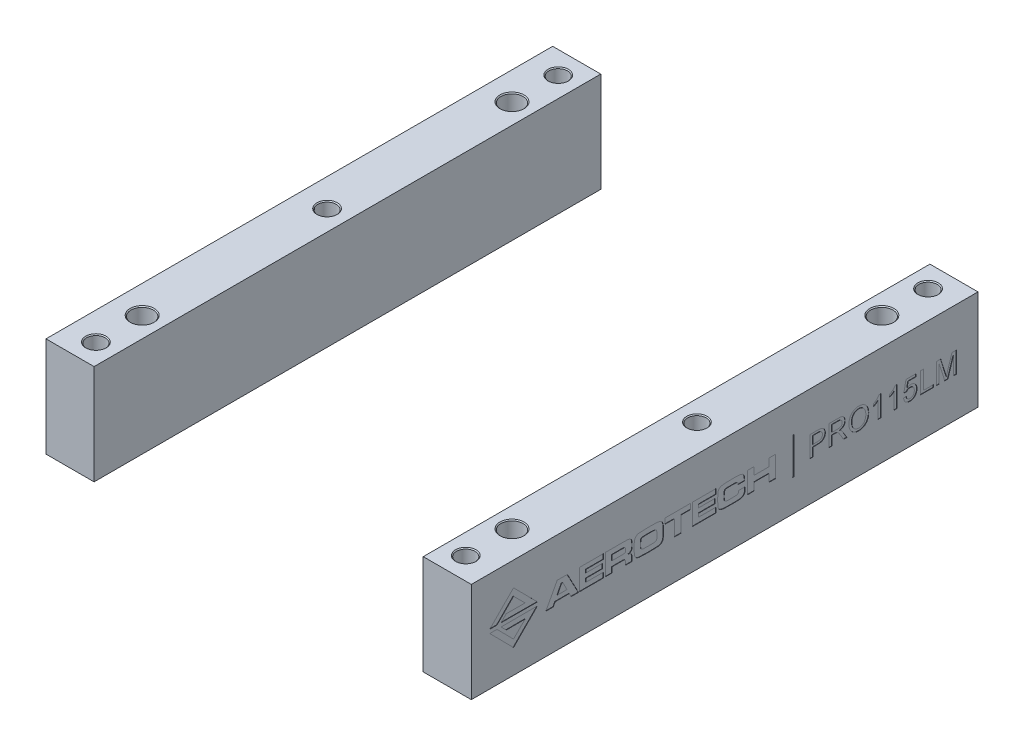
SolidWorks part; units mm, degrees
material "Aluminum Black Anodize"
ref_plane "Front" through (0, 0, 0) normal (0, 0, 1) x (1, 0, 0)
ref_plane "Top" through (0, 0, 0) normal (0, 1, 0) x (1, 0, 0)
ref_plane "Right" through (0, 0, 0) normal (1, 0, 0) x (0, 0, -1)
sketch "Sketch1" plane through (0, 0, 0) normal (0, 0, 1) x (1, 0, 0)
  line L0 (0, 0) -> (0, -37) construction
  line L1 (-57.5, -10) -> (-44.5, -10)
  line L2 (-57.5, -10) -> (-57.5, -37)
  line L3 (-57.5, -37) -> (-44.5, -37)
  line L4 (-44.5, -10) -> (-44.5, -37)
  line L5 (44.5, -10) -> (57.5, -10)
  line L6 (44.5, -10) -> (44.5, -37)
  line L7 (44.5, -37) -> (57.5, -37)
  line L8 (57.5, -10) -> (57.5, -37)
  dimension "D1" = 27
  dimension "D2" = 13
  dimension "D3" = 89
  dimension "D4" = 10
extrude "Extrude1" add sketch "Sketch1" along normal mid plane 137
hole_wizard "M5x0.8 Tapped Hole1" positions "Sketch4" profile "Sketch3" tap size "M5x0.8" standard "ANSI Metric"
sketch "Sketch4" plane through (0, -10, 0) normal (0, 1, 0) x (-1, 0, 0)
  line L0 (50, 62.5) -> (50, -62.5) construction
  line L1 (50, -62.5) -> (-50, -62.5) construction
  line L2 (-50, -62.5) -> (-50, 62.5) construction
  line L3 (-50, 62.5) -> (50, 62.5) construction
  line L4 (50, 62.5) -> (-50, -62.5) construction
  point P0 (50, -62.5)
  point P1 (-50, -62.5)
  point P3 (-50, 0)
  point P5 (50, 0)
  point P7 (50, 62.5)
  point P9 (-50, 62.5)
  dimension "D1" = 100
  dimension "D2" = 125
sketch "Sketch3" plane through (-50, -10, -62.5) normal (1, 0, 0) x (0, 0, 1)
  line L0 (0, 0) -> (0, 9.4618)
  line L1 (0, 9.4618) -> (2.1, 8.2)
  line L2 (2.1, 8.2) -> (2.1, 5.8)
  line L3 (2.1, 5.8) -> (2.5, 5.8)
  line L5 (2.5, 5.8) -> (2.5, 0.25)
  line L6 (2.5, 0.25) -> (2.75, 0)
  line L7 (2.75, 0) -> (0, 0)
  line L8 (-2.5, 0.25) -> (-2.75, 0) construction
  line L10 (0, 9.4618) -> (-2.1, 8.2) construction
  line L11 (0, -6.35) -> (0, 107.95) construction
  dimension "Tap Drill Dia." = 4.2
  dimension "Tap Drill Depth" = 8.2
  dimension "Thread Major Dia." = 5
  dimension "Thread Depth" = 5.8
  dimension "Near C'Sink Dia." = 5.5
  dimension "Near C'Sink Angle" = 90
  dimension "Drill Angle" = 118
hole_wizard "M6x1.0 Tapped Hole1" positions "Sketch6" profile "Sketch5" tap size "M6x1.0" standard "ANSI Metric"
sketch "Sketch6" plane through (0, -10, 0) normal (0, 1, 0) x (-1, 0, 0)
  line L0 (50, -50) -> (-50, -50) construction
  line L1 (-50, -50) -> (-50, 50) construction
  line L2 (-50, 50) -> (50, 50) construction
  line L3 (50, 50) -> (50, -50) construction
  line L4 (50, -50) -> (-50, 50) construction
  point P0 (50, -50)
  point P1 (-50, -50)
  point P3 (-50, 50)
  point P5 (50, 50)
  dimension "D1" = 100
  dimension "D2" = 100
sketch "Sketch5" plane through (-50, -10, -50) normal (1, 0, 0) x (0, 0, 1)
  line L0 (0, 0) -> (0, 11.5022)
  line L1 (0, 11.5022) -> (2.5, 10)
  line L2 (2.5, 10) -> (2.5, 7)
  line L3 (2.5, 7) -> (3, 7)
  line L5 (3, 7) -> (3, 0.25)
  line L6 (3, 0.25) -> (3.25, 0)
  line L7 (3.25, 0) -> (0, 0)
  line L8 (-3, 0.25) -> (-3.25, 0) construction
  line L10 (0, 11.5022) -> (-2.5, 10) construction
  line L11 (0, -6.35) -> (0, 107.95) construction
  dimension "Tap Drill Dia." = 5
  dimension "Tap Drill Depth" = 10
  dimension "Thread Major Dia." = 6
  dimension "Thread Depth" = 7
  dimension "Near C'Sink Dia." = 6.5
  dimension "Near C'Sink Angle" = 90
  dimension "Drill Angle" = 118
sketch "Sketch8" plane through (57.5, 0, 0) normal (1, 0, 0) x (0, 0, -1)
  line L5 (-68.5, -37) -> (-68.5, -10) construction
  line L6 (-68.5, -10) -> (68.5, -10) construction
  line L12 (-63.5, -16.5049) -> (63.5, -16.5049) construction
  line L13 (-63.5, -16.5049) -> (-63.5, -30.4951) construction
  line L14 (-63.5, -30.4951) -> (63.5, -30.4951) construction
  line L15 (63.5, -16.5049) -> (63.5, -30.4951) construction
  line L16 (0, -30.4951) -> (0, -10) construction
  line L17 (-63.5, -23.5) -> (-68.5, -23.5) construction
  line L18 (-48.348, -26.3532) -> (92.4372, -26.3532) construction
  text T0 "PRO115LM" font "Arial" height in points 22
  point P14 (42.2576, 86.3605)
  point P15 (42.2586, 86.3605)
  point P16 (42.2586, 86.3595)
  line B0 (-57.0873, -30.4951) -> (-50.6303, -23.9713)
  line B1 (-50.6303, -23.9713) -> (-60.452, -24.0011)
  line B2 (-60.452, -24.0011) -> (-59.05, -25.4103)
  line B3 (-59.05, -25.4103) -> (-53.9513, -25.3879)
  line B4 (-53.9513, -25.3879) -> (-57.0945, -28.5095)
  line B5 (-57.0945, -28.5095) -> (-61.5671, -24.0011)
  line B6 (-61.5671, -24.0011) -> (-63.5, -24.0083)
  line B7 (-63.5, -24.0083) -> (-57.0873, -30.4951)
  line B8 (-57.0873, -16.5049) -> (-50.6303, -23.0285)
  line B9 (-50.6303, -23.0285) -> (-60.452, -22.9986)
  line B10 (-60.452, -22.9986) -> (-59.05, -21.5893)
  line B11 (-59.05, -21.5893) -> (-53.9513, -21.6119)
  line B12 (-53.9513, -21.6119) -> (-57.0945, -18.4903)
  line B13 (-57.0945, -18.4903) -> (-61.5671, -22.9986)
  line B14 (-61.5671, -22.9986) -> (-63.5, -22.9915)
  line B15 (-63.5, -22.9915) -> (-57.0873, -16.5049)
  line B16 (-41.5139, -26.3532) -> (-42.01, -25.3896)
  line B17 (-42.01, -25.3896) -> (-45.8382, -25.3896)
  line B18 (-45.8382, -25.3896) -> (-46.3343, -26.3532)
  line B19 (-46.3343, -26.3532) -> (-48.348, -26.3532)
  line B20 (-48.348, -26.3532) -> (-45.2787, -20.6469)
  line B21 (-45.2787, -20.6469) -> (-42.5399, -20.6469)
  line B22 (-42.5399, -20.6469) -> (-39.5128, -26.3532)
  line B23 (-39.5128, -26.3532) -> (-41.5139, -26.3532)
  line B24 (-42.6287, -24.137) -> (-43.7439, -21.9743)
  line B25 (-43.7439, -21.9743) -> (-44.0957, -21.9743)
  line B26 (-44.0957, -21.9743) -> (-45.2109, -24.137)
  line B27 (-45.2109, -24.137) -> (-42.6287, -24.137)
  line B28 (-39.2288, -20.6469) -> (-32.8157, -20.6469)
  line B29 (-32.8157, -20.6469) -> (-32.8157, -21.985)
  line B30 (-32.8157, -21.985) -> (-37.4944, -21.985)
  line B31 (-37.4944, -21.985) -> (-37.4944, -22.8094)
  line B32 (-37.4944, -22.8094) -> (-33.0514, -22.8094)
  line B33 (-33.0514, -22.8094) -> (-33.0514, -24.0619)
  line B34 (-33.0514, -24.0619) -> (-37.4944, -24.0619)
  line B35 (-37.4944, -24.0619) -> (-37.4944, -24.9936)
  line B36 (-37.4944, -24.9936) -> (-32.7835, -24.9936)
  line B37 (-32.7835, -24.9936) -> (-32.7835, -26.3532)
  line B38 (-32.7835, -26.3532) -> (-39.2288, -26.3532)
  line B39 (-39.2288, -26.3532) -> (-39.2288, -20.6469)
  line B40 (-32.2072, -26.3532) -> (-32.2072, -20.6469)
  line B41 (-32.2072, -20.6469) -> (-27.9447, -20.6469)
  line B42 (-25.0662, -25.8247) -> (-25.0662, -26.3532)
  line B43 (-25.0662, -26.3532) -> (-26.8005, -26.3532)
  line B44 (-26.8005, -26.3532) -> (-26.8005, -26.0535)
  line B45 (-27.9575, -24.9078) -> (-30.4405, -24.9078)
  line B46 (-30.4405, -24.9078) -> (-30.4405, -26.3532)
  line B47 (-30.4405, -26.3532) -> (-32.2072, -26.3532)
  line B48 (-30.4405, -23.484) -> (-27.9618, -23.484)
  line B49 (-27.9659, -22.0706) -> (-30.4405, -22.0706)
  line B50 (-30.4405, -22.0706) -> (-30.4405, -23.484)
  line B51 (-16.1737, -20.6469) -> (-9.1712, -20.6469)
  line B52 (-9.1712, -20.6469) -> (-9.1712, -22.1028)
  line B53 (-9.1712, -22.1028) -> (-11.7411, -22.1028)
  line B54 (-11.7411, -22.1028) -> (-11.7411, -26.3532)
  line B55 (-11.7411, -26.3532) -> (-13.5932, -26.3532)
  line B56 (-13.5932, -26.3532) -> (-13.5932, -22.1028)
  line B57 (-13.5932, -22.1028) -> (-16.1737, -22.1028)
  line B58 (-16.1737, -22.1028) -> (-16.1737, -20.6469)
  line B59 (-8.7626, -20.6469) -> (-2.3497, -20.6469)
  line B60 (-2.3497, -20.6469) -> (-2.3497, -21.985)
  line B61 (-2.3497, -21.985) -> (-7.0284, -21.985)
  line B62 (-7.0284, -21.985) -> (-7.0284, -22.8094)
  line B63 (-7.0284, -22.8094) -> (-2.5854, -22.8094)
  line B64 (-2.5854, -22.8094) -> (-2.5854, -24.0619)
  line B65 (-2.5854, -24.0619) -> (-7.0284, -24.0619)
  line B66 (-7.0284, -24.0619) -> (-7.0284, -24.9936)
  line B67 (-7.0284, -24.9936) -> (-2.3177, -24.9936)
  line B68 (-2.3177, -24.9936) -> (-2.3177, -26.3532)
  line B69 (-2.3177, -26.3532) -> (-8.7626, -26.3532)
  line B70 (-8.7626, -26.3532) -> (-8.7626, -20.6469)
  line B71 (3.7357, -24.1477) -> (5.4996, -24.1477)
  line B72 (5.4062, -22.6916) -> (3.6426, -22.6916)
  line B73 (6.1269, -20.6469) -> (7.9793, -20.6469)
  line B74 (7.9793, -20.6469) -> (7.9793, -22.6916)
  line B75 (7.9793, -22.6916) -> (11.9619, -22.6916)
  line B76 (11.9619, -22.6916) -> (11.9619, -20.6469)
  line B77 (11.9619, -20.6469) -> (13.8143, -20.6469)
  line B78 (13.8143, -20.6469) -> (13.8143, -26.3532)
  line B79 (13.8143, -26.3532) -> (11.9619, -26.3532)
  line B80 (11.9619, -26.3532) -> (11.9619, -24.2868)
  line B81 (11.9619, -24.2868) -> (7.9793, -24.2868)
  line B82 (7.9793, -24.2868) -> (7.9793, -26.3532)
  line B83 (7.9793, -26.3532) -> (6.1269, -26.3532)
  line B84 (6.1269, -26.3532) -> (6.1269, -20.6469)
  line B85 (18.7267, -28.3892) -> (18.3739, -28.3892)
  line B86 (18.3739, -28.3892) -> (18.3739, -18.5115)
  line B87 (18.3739, -18.5115) -> (18.7267, -18.5115)
  line B88 (18.7267, -18.5115) -> (18.7267, -28.3892)
  spline B89 degree 3 poles (-27.9447, -20.6469) (-26.9455, -20.6495) (-26.3471, -20.6595) (-26.1495, -20.6765) knots 2 2 2 2 3 3 3 3
  spline B90 degree 3 poles (-26.1495, -20.6765) (-25.9517, -20.6936) (-25.7614, -20.7587) (-25.5776, -20.8721) knots 3 3 3 3 4 4 4 4
  spline B91 degree 3 poles (-25.5776, -20.8721) (-25.3576, -21.0023) (-25.2067, -21.183) (-25.1248, -21.414) knots 4 4 4 4 5 5 5 5
  spline B92 degree 3 poles (-25.1248, -21.414) (-25.0429, -21.6448) (-25.0019, -22.007) (-25.0019, -22.4999) knots 5 5 5 5 6 6 6 6
  spline B93 degree 3 poles (-25.0019, -22.4999) (-25.0019, -22.9164) (-25.028, -23.2226) (-25.0801, -23.4182) knots 6 6 6 6 7 7 7 7
  spline B94 degree 3 poles (-25.0801, -23.4182) (-25.1323, -23.6137) (-25.2307, -23.7711) (-25.3745, -23.8901) knots 7 7 7 7 8 8 8 8
  spline B95 degree 3 poles (-25.3745, -23.8901) (-25.5295, -24.0143) (-25.7642, -24.1008) (-26.0773, -24.149) knots 8 8 8 8 9 9 9 9
  spline B96 degree 3 poles (-26.0773, -24.149) (-25.708, -24.1777) (-25.4427, -24.2819) (-25.282, -24.462) knots 9 9 9 9 10 10 10 10
  spline B97 degree 3 poles (-25.282, -24.462) (-25.1888, -24.5697) (-25.1296, -24.7008) (-25.1044, -24.856) knots 10 10 10 10 11 11 11 11
  spline B98 degree 3 poles (-25.1044, -24.856) (-25.0789, -25.011) (-25.0662, -25.334) (-25.0662, -25.8247) knots 11 11 11 11 12 12 12 12
  spline B99 degree 3 poles (-26.8005, -26.0535) (-26.8005, -25.735) (-26.8125, -25.5081) (-26.8366, -25.3729) knots 15 15 15 15 16 16 16 16
  spline B100 degree 3 poles (-26.8366, -25.3729) (-26.8607, -25.2377) (-26.905, -25.1345) (-26.9699, -25.0644) knots 16 16 16 16 17 17 17 17
  spline B101 degree 3 poles (-26.9699, -25.0644) (-27.0351, -24.9969) (-27.1248, -24.9538) (-27.2392, -24.9354) knots 17 17 17 17 18 18 18 18
  spline B102 degree 3 poles (-27.2392, -24.9354) (-27.3535, -24.9171) (-27.5931, -24.9078) (-27.9575, -24.9078) knots 18 18 18 18 19 19 19 19
  spline B103 degree 3 poles (-27.9618, -23.484) (-27.5341, -23.4753) (-27.2791, -23.4676) (-27.1965, -23.4604) knots 1 1 1 1 2 2 2 2
  spline B104 degree 3 poles (-27.1965, -23.4604) (-27.1139, -23.4535) (-27.0435, -23.4314) (-26.9846, -23.3942) knots 2 2 2 2 3 3 3 3
  spline B105 degree 3 poles (-26.9846, -23.3942) (-26.9091, -23.3488) (-26.8563, -23.2792) (-26.8254, -23.1851) knots 3 3 3 3 4 4 4 4
  spline B106 degree 3 poles (-26.8254, -23.1851) (-26.7946, -23.0911) (-26.7791, -22.9488) (-26.7791, -22.7581) knots 4 4 4 4 5 5 5 5
  spline B107 degree 3 poles (-26.7791, -22.7581) (-26.7791, -22.5674) (-26.7968, -22.4258) (-26.8318, -22.3333) knots 5 5 5 5 6 6 6 6
  spline B108 degree 3 poles (-26.8318, -22.3333) (-26.8666, -22.2408) (-26.9272, -22.1745) (-27.014, -22.1347) knots 6 6 6 6 7 7 7 7
  spline B109 degree 3 poles (-27.014, -22.1347) (-27.0757, -22.1063) (-27.1489, -22.0892) (-27.2342, -22.0835) knots 7 7 7 7 8 8 8 8
  spline B110 degree 3 poles (-27.2342, -22.0835) (-27.3196, -22.078) (-27.5636, -22.0737) (-27.9659, -22.0706) knots 8 8 8 8 9 9 9 9
  spline B111 degree 3 poles (-23.0861, -20.6547) (-22.6197, -20.5925) (-21.7603, -20.5611) (-20.5078, -20.5611) knots 11 11 11 11 12 12 12 12
  spline B112 degree 3 poles (-24.3286, -21.6016) (-24.1758, -21.0581) (-23.7619, -20.7425) (-23.0861, -20.6547) knots 10 10 10 10 11 11 11 11
  spline B113 degree 3 poles (-24.3286, -25.4025) (-24.433, -25.0291) (-24.4852, -24.3831) (-24.4852, -23.4661) (-24.4852, -22.5941) (-24.433, -21.9726) (-24.3286, -21.6016) knots 8 8 8 8 9 9 9 10 10 10 10
  spline B114 degree 3 poles (-23.0861, -26.3539) (-23.7619, -26.2633) (-24.1758, -25.9463) (-24.3286, -25.4025) knots 7 7 7 7 8 8 8 8
  spline B115 degree 3 poles (-17.9298, -26.3539) (-18.3992, -26.4106) (-19.2527, -26.4386) (-20.4907, -26.4386) (-21.752, -26.4386) (-22.6169, -26.4106) (-23.0861, -26.3539) knots 5 5 5 5 6 6 6 7 7 7 7
  spline B116 degree 3 poles (-16.6874, -25.4025) (-16.8402, -25.9463) (-17.2544, -26.2633) (-17.9298, -26.3539) knots 4 4 4 4 5 5 5 5
  spline B117 degree 3 poles (-16.6874, -21.6016) (-16.5826, -21.9755) (-16.5305, -22.6084) (-16.5305, -23.5002) (-16.5305, -24.3947) (-16.5826, -25.0291) (-16.6874, -25.4025) knots 2 2 2 2 3 3 3 4 4 4 4
  spline B118 degree 3 poles (-17.9298, -20.6547) (-17.2544, -20.7425) (-16.8402, -21.0581) (-16.6874, -21.6016) knots 1 1 1 1 2 2 2 2
  spline B119 degree 3 poles (-20.5078, -20.5611) (-19.2588, -20.5611) (-18.3992, -20.5925) (-17.9298, -20.6547) knots 0 0 0 0 1 1 1 1
  spline B120 degree 3 poles (-18.9535, -22.0939) (-19.1682, -22.0641) (-19.6848, -22.0493) (-20.5037, -22.0493) knots 13 13 13 13 14 14 14 14
  spline B121 degree 3 poles (-18.4917, -22.3214) (-18.5853, -22.1994) (-18.7389, -22.1237) (-18.9535, -22.0939) knots 12 12 12 12 13 13 13 13
  spline B122 degree 3 poles (-18.3393, -22.7571) (-18.3677, -22.5631) (-18.4185, -22.4175) (-18.4917, -22.3214) knots 11 11 11 11 12 12 12 12
  spline B123 degree 3 poles (-18.3522, -24.4107) (-18.3155, -24.2593) (-18.2969, -24.0092) (-18.2969, -23.6605) (-18.2969, -23.2523) (-18.3114, -22.9512) (-18.3393, -22.7571) knots 9 9 9 9 10 10 10 11 11 11 11
  spline B124 degree 3 poles (-18.5596, -24.7573) (-18.458, -24.6779) (-18.3889, -24.5626) (-18.3522, -24.4107) knots 8 8 8 8 9 9 9 9
  spline B125 degree 3 poles (-19.0808, -24.9231) (-18.8464, -24.8977) (-18.6726, -24.8424) (-18.5596, -24.7573) knots 7 7 7 7 8 8 8 8
  spline B126 degree 3 poles (-22.0243, -24.9106) (-21.7613, -24.9445) (-21.2518, -24.9614) (-20.4949, -24.9614) (-19.7864, -24.9614) (-19.3149, -24.9488) (-19.0808, -24.9231) knots 5 5 5 5 6 6 6 7 7 7 7
  spline B127 degree 3 poles (-22.6636, -24.413) (-22.5931, -24.7051) (-22.3799, -24.8706) (-22.0243, -24.9106) knots 4 4 4 4 5 5 5 5
  spline B128 degree 3 poles (-22.6171, -22.4935) (-22.6848, -22.6876) (-22.7187, -23.0752) (-22.7187, -23.6562) (-22.7187, -24.0049) (-22.7003, -24.2571) (-22.6636, -24.413) knots 2 2 2 2 3 3 3 4 4 4 4
  spline B129 degree 3 poles (-22.1892, -22.1216) (-22.4066, -22.1754) (-22.5494, -22.2995) (-22.6171, -22.4935) knots 1 1 1 1 2 2 2 2
  spline B130 degree 3 poles (-20.5037, -22.0493) (-21.4385, -22.0493) (-22, -22.0734) (-22.1892, -22.1216) knots 0 0 0 0 1 1 1 1
  spline B131 degree 3 poles (5.4996, -24.1477) (5.5082, -24.4253) (5.5126, -24.6055) (5.5126, -24.6877) knots 1 1 1 1 2 2 2 2
  spline B132 degree 3 poles (5.5126, -24.6877) (5.5126, -25.1297) (5.4461, -25.4752) (5.3135, -25.7247) knots 2 2 2 2 3 3 3 3
  spline B133 degree 3 poles (5.3135, -25.7247) (5.1668, -26.0025) (4.8798, -26.1908) (4.4529, -26.2902) knots 3 3 3 3 4 4 4 4
  spline B134 degree 3 poles (4.4529, -26.2902) (4.0268, -26.3892) (3.2899, -26.4386) (2.2419, -26.4386) knots 4 4 4 4 5 5 5 5
  spline B135 degree 3 poles (2.2419, -26.4386) (1.1401, -26.4386) (0.355, -26.4187) (-0.1121, -26.3796) knots 5 5 5 5 6 6 6 6
  spline B136 degree 3 poles (-0.1121, -26.3796) (-0.5797, -26.3401) (-0.9318, -26.2595) (-1.1695, -26.1377) knots 6 6 6 6 7 7 7 7
  spline B137 degree 3 poles (-1.1695, -26.1377) (-1.3813, -26.0306) (-1.5395, -25.8847) (-1.6438, -25.7012) knots 7 7 7 7 8 8 8 8
  spline B138 degree 3 poles (-1.6438, -25.7012) (-1.7482, -25.5174) (-1.8161, -25.2644) (-1.8471, -24.9421) knots 8 8 8 8 9 9 9 9
  spline B139 degree 3 poles (-1.8471, -24.9421) (-1.8729, -24.6848) (-1.885, -24.2167) (-1.885, -23.5381) knots 9 9 9 9 10 10 10 10
  spline B140 degree 3 poles (-1.885, -23.5381) (-1.885, -22.8768) (-1.8729, -22.3996) (-1.8471, -22.107) knots 10 10 10 10 11 11 11 11
  spline B141 degree 3 poles (-1.8471, -22.107) (-1.822, -21.8143) (-1.7724, -21.5876) (-1.6986, -21.4264) knots 11 11 11 11 12 12 12 12
  spline B142 degree 3 poles (-1.6986, -21.4264) (-1.5377, -21.0645) (-1.2118, -20.8299) (-0.7206, -20.7222) knots 12 12 12 12 13 13 13 13
  spline B143 degree 3 poles (-0.7206, -20.7222) (-0.229, -20.6151) (0.7622, -20.5611) (2.2539, -20.5611) knots 13 13 13 13 14 14 14 14
  spline B144 degree 3 poles (2.2539, -20.5611) (2.9988, -20.5611) (3.5417, -20.5773) (3.8807, -20.6097) knots 14 14 14 14 15 15 15 15
  spline B145 degree 3 poles (3.8807, -20.6097) (4.2194, -20.6421) (4.4888, -20.7052) (4.6896, -20.7984) knots 15 15 15 15 16 16 16 16
  spline B146 degree 3 poles (4.6896, -20.7984) (4.9525, -20.9198) (5.1371, -21.1013) (5.2446, -21.3427) knots 16 16 16 16 17 17 17 17
  spline B147 degree 3 poles (5.2446, -21.3427) (5.3518, -21.584) (5.4059, -21.9392) (5.4059, -22.4079) knots 17 17 17 17 18 18 18 18
  spline B148 degree 3 poles (5.4059, -22.4079) (5.4059, -22.4334) (5.4059, -22.5278) (5.4062, -22.6916) knots 18 18 18 18 19 19 19 19
  spline B149 degree 3 poles (3.6426, -22.6916) (3.634, -22.5026) (3.622, -22.3758) (3.6065, -22.3109) knots 20 20 20 20 21 21 21 21
  spline B150 degree 3 poles (3.6065, -22.3109) (3.591, -22.246) (3.5593, -22.1938) (3.5114, -22.1542) knots 21 21 21 21 22 22 22 22
  spline B151 degree 3 poles (3.5114, -22.1542) (3.4432, -22.0951) (3.2726, -22.052) (2.9988, -22.0251) knots 22 22 22 22 23 23 23 23
  spline B152 degree 3 poles (2.9988, -22.0251) (2.7245, -21.9986) (2.3097, -21.985) (1.7534, -21.985) knots 23 23 23 23 24 24 24 24
  spline B153 degree 3 poles (1.7534, -21.985) (1.2025, -21.985) (0.8215, -21.9971) (0.61, -22.021) knots 24 24 24 24 25 25 25 25
  spline B154 degree 3 poles (0.61, -22.021) (0.3981, -22.0453) (0.2485, -22.0911) (0.161, -22.159) knots 25 25 25 25 26 26 26 26
  spline B155 degree 3 poles (0.161, -22.159) (0.0563, -22.2441) (-0.0167, -22.3853) (-0.0574, -22.5834) knots 26 26 26 26 27 27 27 27
  spline B156 degree 3 poles (-0.0574, -22.5834) (-0.098, -22.7814) (-0.1187, -23.0969) (-0.1187, -23.5296) knots 27 27 27 27 28 28 28 28
  spline B157 degree 3 poles (-0.1187, -23.5296) (-0.1187, -23.9627) (-0.1004, -24.2674) (-0.0639, -24.4441) knots 28 28 28 28 29 29 29 29
  spline B158 degree 3 poles (-0.0639, -24.4441) (-0.0267, -24.621) (0.0439, -24.7494) (0.148, -24.8282) knots 29 29 29 29 30 30 30 30
  spline B159 degree 3 poles (0.148, -24.8282) (0.2465, -24.902) (0.4046, -24.9512) (0.6206, -24.9767) knots 30 30 30 30 31 31 31 31
  spline B160 degree 3 poles (0.6206, -24.9767) (0.8359, -25.0022) (1.2184, -25.0148) (1.7661, -25.0148) knots 31 31 31 31 32 32 32 32
  spline B161 degree 3 poles (1.7661, -25.0148) (2.441, -25.0148) (2.8906, -25.0034) (3.1156, -24.9809) knots 32 32 32 32 33 33 33 33
  spline B162 degree 3 poles (3.1156, -24.9809) (3.3398, -24.958) (3.4914, -24.9096) (3.5706, -24.8357) knots 33 33 33 33 34 34 34 34
  spline B163 degree 3 poles (3.5706, -24.8357) (3.6754, -24.7359) (3.7298, -24.5067) (3.7357, -24.1477) knots 34 34 34 34 35 35 35 35
  dimension "D1" = 127
  dimension "D2" = 4
sketch_block_instance "BLOCK 3_0-2"
sketch_block "BLOCK 3_0"
extrude "Cut-Extrude1" cut sketch "Sketch8" against normal blind 0.1
